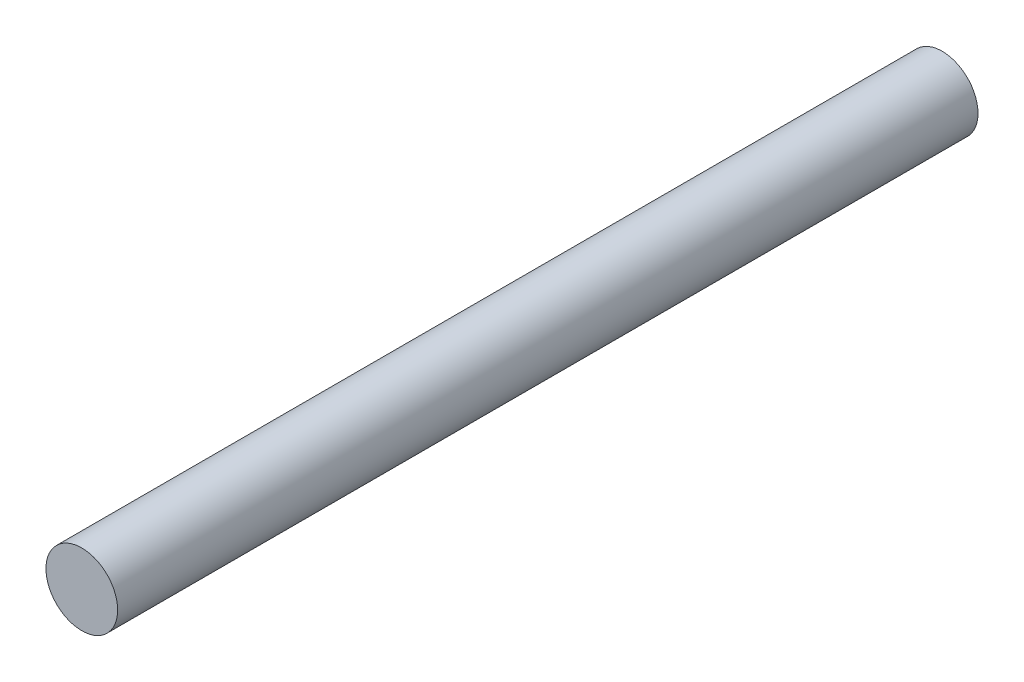
SolidWorks part; units mm, degrees
ref_plane "Plan de face" through (0, 0, 0) normal (0, 0, 1) x (1, 0, 0)
ref_plane "Plan de dessus" through (0, 0, 0) normal (0, 1, 0) x (1, 0, 0)
ref_plane "Plan de droite" through (0, 0, 0) normal (1, 0, 0) x (0, 0, -1)
sketch "Esquisse1" plane through (0, 0, 0) normal (0, 0, 1) x (1, 0, 0)
  circle A0 centre (0, 0) radius 2.5
  dimension "D1" = 5
extrude "Boss.-Extru.1" add sketch "Esquisse1" along normal blind 60
